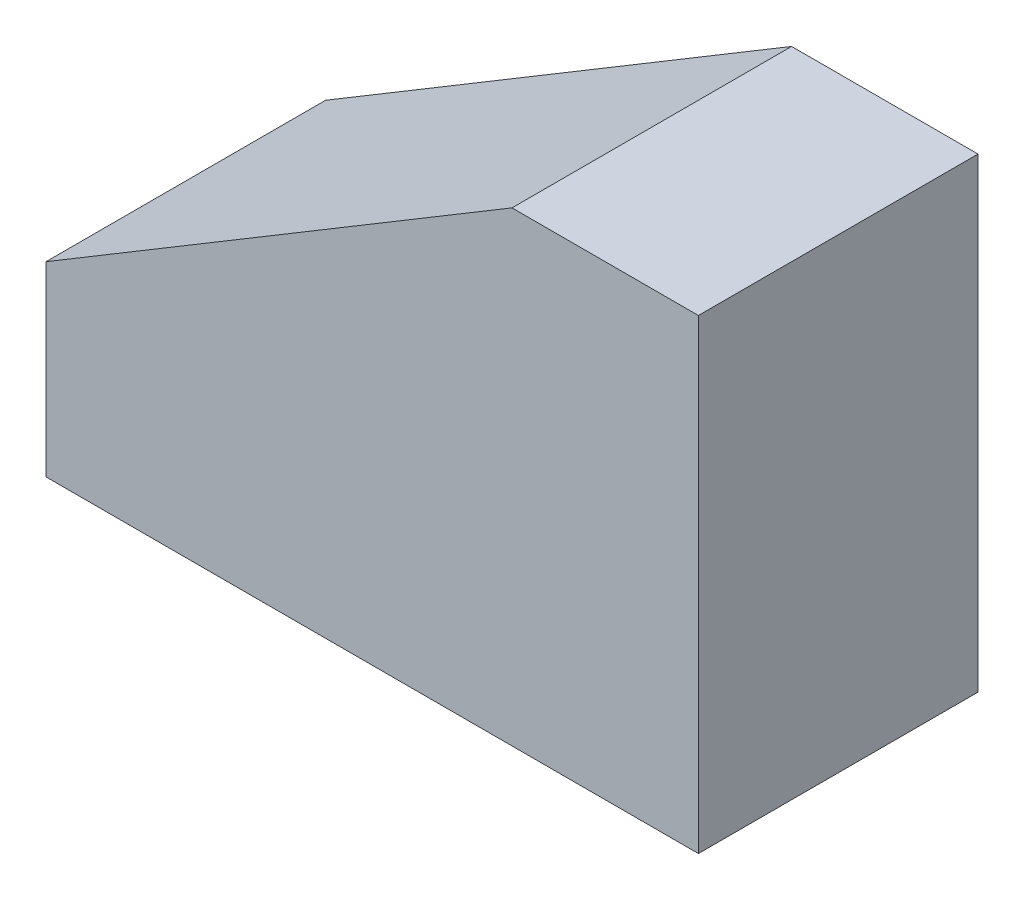
SolidWorks part; units mm, degrees
ref_plane "Front Plane" through (0, 0, 0) normal (0, 0, 1) x (1, 0, 0)
ref_plane "Top Plane" through (0, 0, 0) normal (0, 1, 0) x (1, 0, 0)
ref_plane "Right Plane" through (0, 0, 0) normal (1, 0, 0) x (0, 0, -1)
sketch "Sketch1" plane through (0, 0, 0) normal (0, 0, 1) x (1, 0, 0)
  line L0 (0, 0) -> (35, 0)
  line L1 (35, 0) -> (35, 25)
  line L2 (35, 25) -> (25, 25)
  line L3 (25, 25) -> (0, 10)
  line L4 (0, 10) -> (0, 0)
  dimension "D1" = 35
  dimension "D2" = 25
  dimension "D3" = 10
  dimension "D4" = 10
extrude "Boss-Extrude1" add sketch "Sketch1" along normal blind 15
